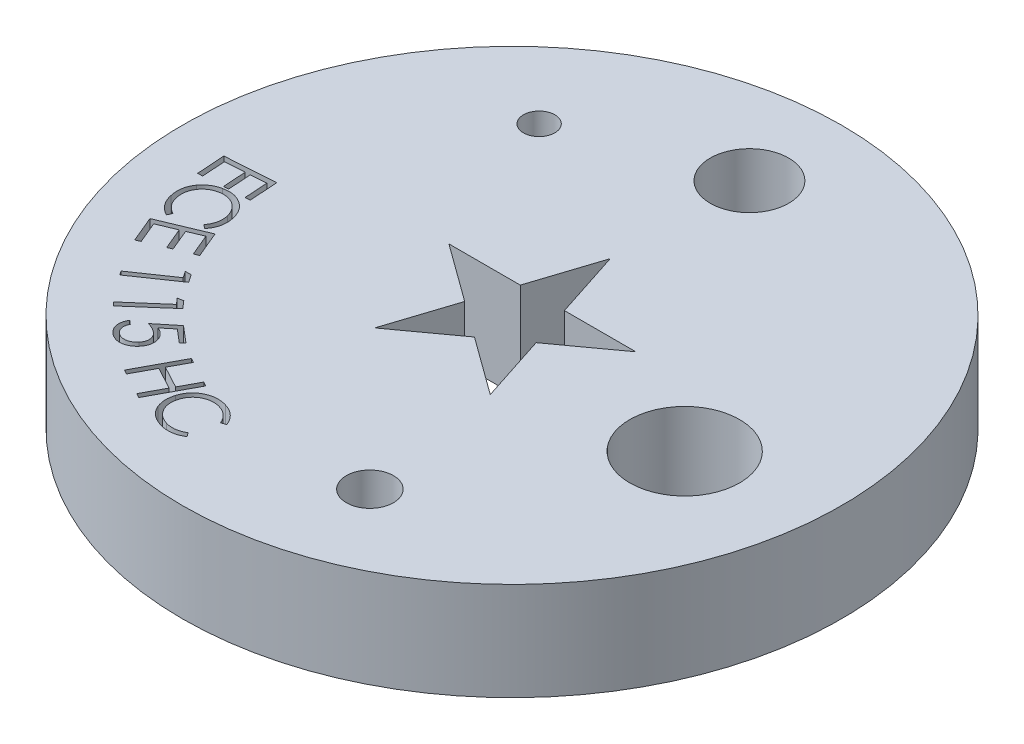
SolidWorks part; units mm, degrees
ref_plane "Front Plane" through (0, 0, 0) normal (0, 0, 1) x (1, 0, 0)
ref_plane "Top Plane" through (0, 0, 0) normal (0, 1, 0) x (1, 0, 0)
ref_plane "Right Plane" through (0, 0, 0) normal (1, 0, 0) x (0, 0, -1)
sketch "Sketch1" plane through (0, 0, 0) normal (0, 1, 0) x (1, 0, 0)
  circle A0 centre (0, 0) radius 21
  dimension "D1" = 42
extrude "Boss-Extrude1" add sketch "Sketch1" along normal blind 6.25
sketch "Sketch2" plane through (0, 6.25, 0) normal (0, 1, 0) x (1, 0, 0)
  line L0 (0, 0) -> (0, 6.261) construction
  line L6 (0, 6.261) -> (-1.4057, 1.9348)
  line L7 (0, 6.261) -> (-5.9546, 1.9348) construction
  line L8 (-5.9546, 1.9348) -> (-3.6801, -5.0652) construction
  line L9 (-3.6801, -5.0652) -> (3.6801, -5.0652) construction
  line L10 (3.6801, -5.0652) -> (5.9546, 1.9348) construction
  line L11 (5.9546, 1.9348) -> (0, 6.261) construction
  line L12 (-3.6801, -5.0652) -> (0, -2.3915)
  line L13 (5.9546, 1.9348) -> (1.4057, 1.9348)
  line L14 (-5.9546, 1.9348) -> (-2.2744, -0.739)
  line L15 (3.6801, -5.0652) -> (2.2744, -0.739)
  line L16 (-2.2744, -0.739) -> (-3.6801, -5.0652)
  line L17 (-1.4057, 1.9348) -> (-5.9546, 1.9348)
  line L18 (1.4057, 1.9348) -> (0, 6.261)
  line L19 (2.2744, -0.739) -> (5.9546, 1.9348)
  line L20 (0, -2.3915) -> (3.6801, -5.0652)
  circle A0 centre (0, 0) radius 5.0652 construction
  dimension "D1" = 7
extrude "Cut-Extrude1" cut sketch "Sketch2" against normal through all
sketch "Sketch3" plane through (0, 6.25, 0) normal (0, 1, 0) x (1, 0, 0)
  circle A0 centre (-9.7067, 11.4359) radius 1
  point P2 (0, 0)
  dimension "D1" = 2
  dimension "D2" = 15
  dimension "D3" = 11
extrude "Cut-Extrude2" cut sketch "Sketch3" against normal through all
sketch "Sketch5" plane through (0, 6.25, 0) normal (0, 1, 0) x (1, 0, 0)
  circle A0 centre (0.1316, 15) radius 2.5
  point P2 (0, 15)
  dimension "D1" = 5
  dimension "D2" = 15
  dimension "D3" = 8.74
extrude "Cut-Extrude3" cut sketch "Sketch5" against normal through all
sketch "Sketch6" plane through (0, 6.25, 0) normal (0, 1, 0) x (1, 0, 0)
  circle A0 centre (13, -1.9949) radius 3.5
  dimension "D1" = 7
  dimension "D2" = 13
  dimension "D3" = 15.4
extrude "Cut-Extrude4" cut sketch "Sketch6" against normal through all
sketch "Sketch7" plane through (0, 6.25, 0) normal (0, 1, 0) x (1, 0, 0)
  circle A0 centre (5.0645, -14.1192) radius 1.5
  dimension "D1" = 3
  dimension "D2" = 15
  dimension "D3" = 21
extrude "Cut-Extrude5" cut sketch "Sketch7" against normal through all
sketch "Sketch8" plane through (0, 6.25, 0) normal (0, 1, 0) x (1, 0, 0)
  arc A0 (-18, 0) -> (0, -18) centre (0, 0) ccw construction
  text T0 "ECE 115 HC"
  point P5 (6.553, -16.8583)
  point P6 (-18.1363, 0.3263)
  point P7 (-16.9943, 8.8098)
  point P8 (-18.1907, 2.5559)
  point P9 (-6.4442, -17.674)
  point P10 (-17.8644, -0.5982)
  point P11 (-18.245, 2.1209)
  point P12 (-4.3233, -18.0003)
  point P13 (-12.7279, -12.7279)
  dimension "D3" = 18
  dimension "D1" = 18
  dimension "D2" = 18
extrude "Cut-Extrude6" cut sketch "Sketch8" against normal through all
